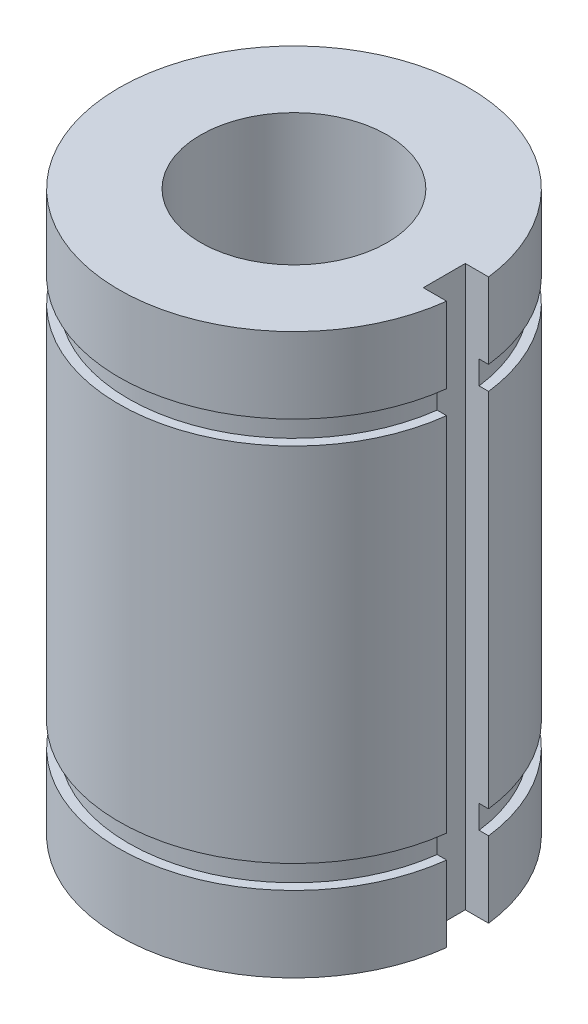
SolidWorks part; units mm, degrees
ref_plane "Alzado" through (0, 0, 0) normal (0, 0, 1) x (1, 0, 0)
ref_plane "Planta" through (0, 0, 0) normal (0, 1, 0) x (1, 0, 0)
ref_plane "Vista lateral" through (0, 0, 0) normal (1, 0, 0) x (0, 0, -1)
sketch "Croquis1" plane through (0, 0, 0) normal (0, 1, 0) x (1, 0, 0)
  circle A0 centre (0, 0) radius 7.5
  circle A1 centre (0, 0) radius 4
  dimension "D1" = 15
  dimension "D2" = 8
extrude "Saliente-Extruir1" add sketch "Croquis1" along normal blind 24
sketch "Croquis2" plane through (0, 0, 0) normal (0, -1, 0) x (1, 0, 0)
  line L0 (7.4458, 0.9) -> (7.4458, -0.9) construction
  line L1 (8.4458, -0.9) -> (6.4458, -0.9)
  line L2 (8.4458, -0.9) -> (8.4458, 0.9)
  line L3 (8.4458, 0.9) -> (6.4458, 0.9)
  line L4 (6.4458, -0.9) -> (6.4458, 0.9)
  circle A2 centre (0, 0) radius 7.5 construction
  dimension "D1" = 1.8
  dimension "D2" = 2
  dimension "D3" = 0.9
extrude "Cortar-Extruir1" cut sketch "Croquis2" against normal through all
sketch "Croquis3" plane through (0, 0, 0) normal (0, 0, 1) x (1, 0, 0)
  line L0 (7.4458, 0) -> (7.4458, 24) construction
  line L1 (8.0958, 20.75) -> (7.0958, 20.75)
  line L2 (8.0958, 20.75) -> (8.0958, 19.75)
  line L3 (8.0958, 19.75) -> (7.0958, 19.75)
  line L4 (7.0958, 20.75) -> (7.0958, 19.75)
  line L5 (7.4458, 24) -> (6.4458, 24) construction
  line L6 (-7.5, 12) -> (7.4458, 12) construction
  line L7 (-7.5, 24) -> (-7.5, 0) construction
  line L8 (8.0958, 4.25) -> (7.0958, 4.25)
  line L9 (8.0958, 3.25) -> (7.0958, 3.25)
  line L10 (8.0958, 3.25) -> (8.0958, 4.25)
  line L11 (7.0958, 3.25) -> (7.0958, 4.25)
  line L12 (0, 24) -> (0, 0) construction
  line L13 (4, 24) -> (-4, 24) construction
  line L14 (-7.0958, 3.25) -> (-7.0958, 4.25)
  line L15 (-8.0958, 3.25) -> (-7.0958, 3.25)
  line L16 (-8.0958, 3.25) -> (-8.0958, 4.25)
  line L17 (-8.0958, 4.25) -> (-7.0958, 4.25)
  line L18 (-7.0958, 20.75) -> (-7.0958, 19.75)
  line L19 (-8.0958, 20.75) -> (-8.0958, 19.75)
  line L20 (-8.0958, 19.75) -> (-7.0958, 19.75)
  line L21 (-8.0958, 20.75) -> (-7.0958, 20.75)
  dimension "D1" = 1
  dimension "D2" = 1
  dimension "D3" = 3.25
  dimension "D4" = 0.35
sweep "Cortar-Barrer3" cut profiles "Croquis3" path edge at (0, 24, 4)
